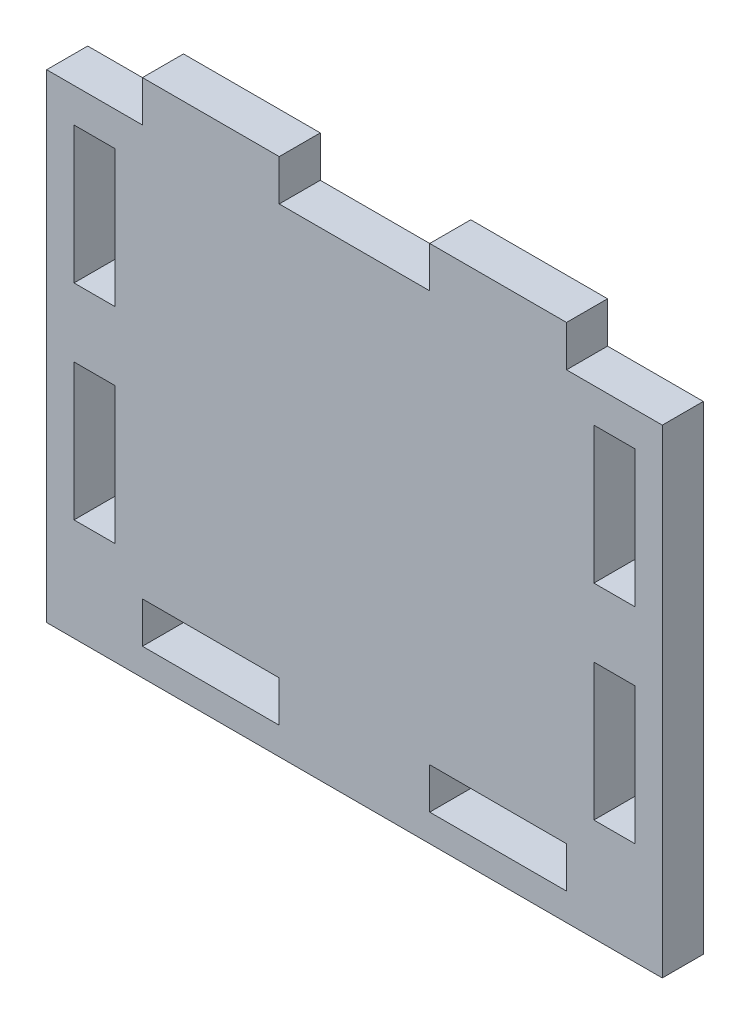
SolidWorks part; units mm, degrees
ref_plane "前视基准面" through (0, 0, 0) normal (0, 0, 1) x (1, 0, 0)
ref_plane "上视基准面" through (0, 0, 0) normal (0, 1, 0) x (1, 0, 0)
ref_plane "右视基准面" through (0, 0, 0) normal (1, 0, 0) x (0, 0, -1)
sketch "草图1" plane through (0, 0, 0) normal (0, 0, 1) x (1, 0, 0)
  line L0 (0, -55) -> (0, 55) construction
  line L1 (-22.5, 15) -> (-15.5, 15)
  line L2 (-22.5, 15) -> (-22.5, -15)
  line L4 (22.5, 15) -> (22.5, -15)
  line L5 (-22.5, 15) -> (22.5, -15) construction
  line L6 (-22.5, -15) -> (22.5, 15) construction
  line L7 (-15.5, -15) -> (-5.5, -15)
  line L8 (-15.5, -15) -> (-15.5, -18)
  line L9 (-15.5, -18) -> (-5.5, -18)
  line L10 (-5.5, -15) -> (-5.5, -18)
  line L11 (-17.5, -12.5) -> (-20.5, -12.5)
  line L12 (-17.5, -12.5) -> (-17.5, -2.5)
  line L13 (-17.5, -2.5) -> (-20.5, -2.5)
  line L14 (-20.5, -12.5) -> (-20.5, -2.5)
  line L15 (15.5, -18) -> (5.5, -18)
  line L16 (5.5, -15) -> (5.5, -18)
  line L17 (15.5, -15) -> (5.5, -15)
  line L18 (15.5, -15) -> (15.5, -18)
  line L19 (55, 0) -> (-55, 0) construction
  line L20 (-17.5, 2.5) -> (-20.5, 2.5)
  line L21 (-20.5, 12.5) -> (-20.5, 2.5)
  line L22 (-17.5, 12.5) -> (-20.5, 12.5)
  line L23 (-17.5, 12.5) -> (-17.5, 2.5)
  line L24 (17.5, -2.5) -> (20.5, -2.5)
  line L25 (20.5, -12.5) -> (20.5, -2.5)
  line L26 (17.5, -12.5) -> (20.5, -12.5)
  line L27 (17.5, -12.5) -> (17.5, -2.5)
  line L28 (17.5, 12.5) -> (17.5, 2.5)
  line L29 (17.5, 12.5) -> (20.5, 12.5)
  line L30 (20.5, 12.5) -> (20.5, 2.5)
  line L31 (17.5, 2.5) -> (20.5, 2.5)
  line L32 (15.5, 15) -> (15.5, 18)
  line L34 (5.5, 15) -> (5.5, 18)
  line L35 (15.5, 18) -> (5.5, 18)
  line L36 (-15.5, 18) -> (-5.5, 18)
  line L37 (-5.5, 15) -> (-5.5, 18)
  line L39 (-15.5, 15) -> (-15.5, 18)
  line L40 (-22.5, -15) -> (-22.5, -20)
  line L41 (-22.5, -20) -> (22.5, -20)
  line L42 (22.5, -20) -> (22.5, -15)
  line L43 (-5.5, 15) -> (5.5, 15)
  line L44 (15.5, 15) -> (22.5, 15)
  point P0 (0, 0)
  dimension "D1" = 45
  dimension "D2" = 30
  dimension "D3" = 10
  dimension "D4" = 3
  dimension "D5" = 10
  dimension "D6" = 3
  dimension "D8" = 2
  dimension "D9" = 7
extrude "凸台-拉伸1" add sketch "草图1" along normal blind 3
